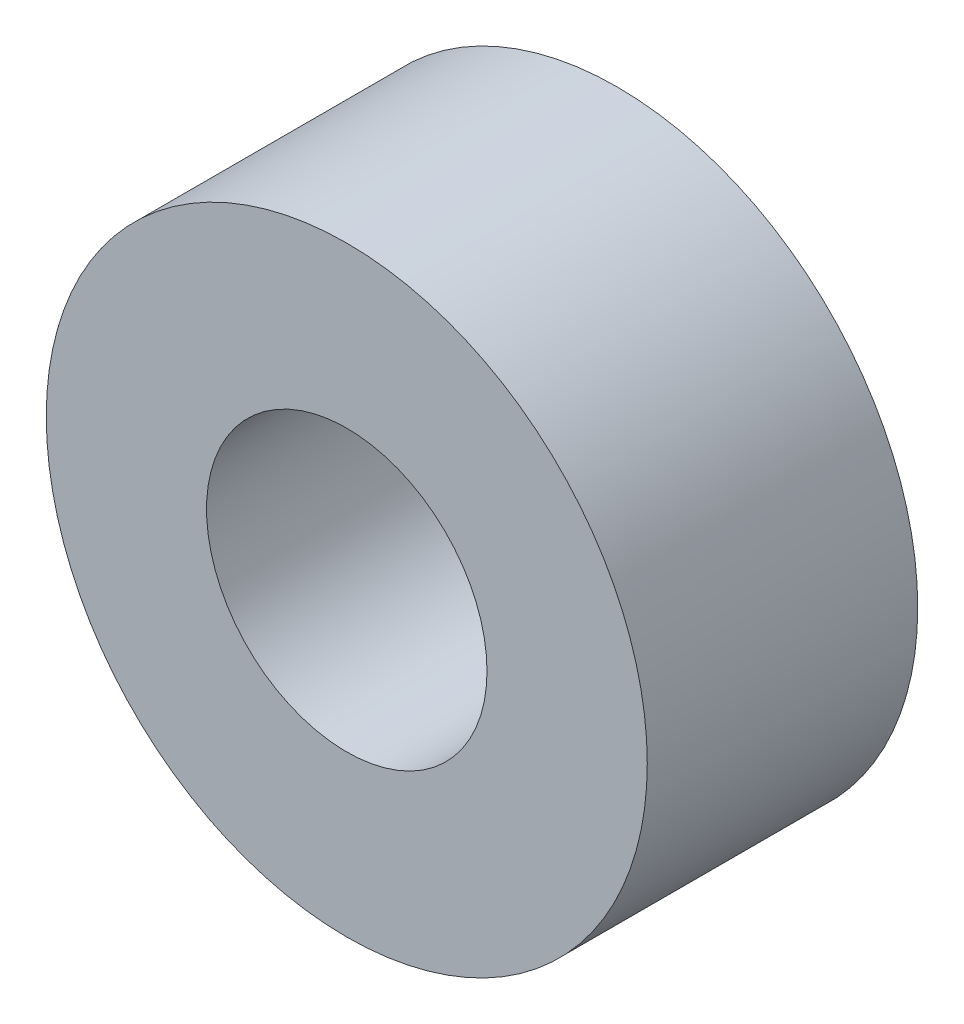
SolidWorks part; units mm, degrees
material "1060 合金"
ref_plane "前视基准面" through (0, 0, 0) normal (0, 0, 1) x (1, 0, 0)
ref_plane "上视基准面" through (0, 0, 0) normal (0, 1, 0) x (1, 0, 0)
ref_plane "右视基准面" through (0, 0, 0) normal (1, 0, 0) x (0, 0, -1)
sketch "草图1" plane through (0, 0, 0) normal (0, 0, 1) x (1, 0, 0)
  circle A0 centre (0, 0) radius 60
  circle A1 centre (0, 0) radius 28 construction
  circle A2 centre (0, 0) radius 28
  dimension "D1" = 120
extrude "凸台-拉伸1" add sketch "草图1" against normal blind 52 and the other way blind 2
